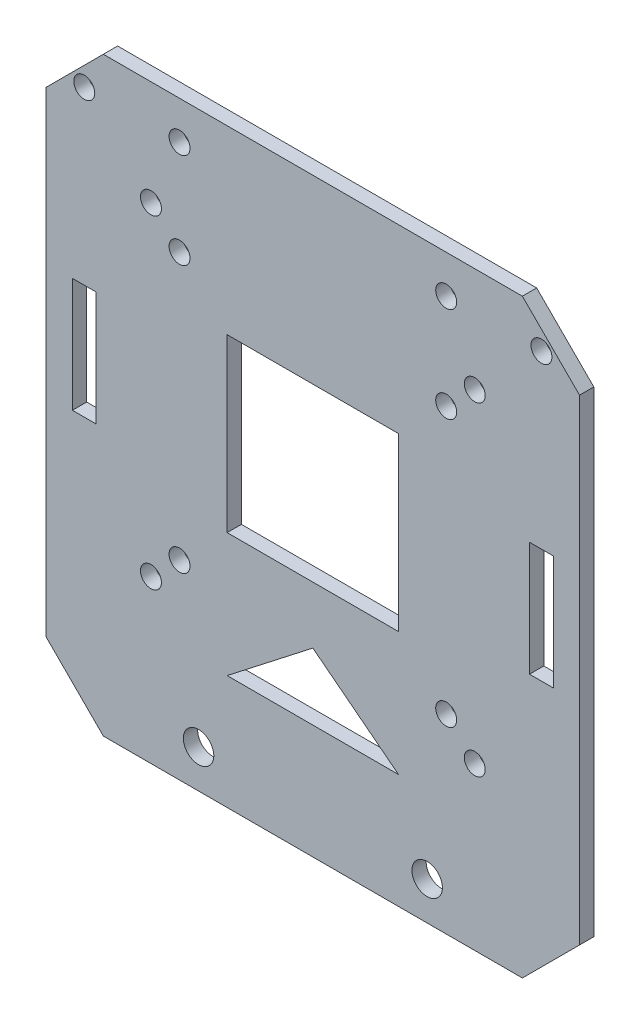
SolidWorks part; units mm, degrees
material "碳纤维板_1600kg_m3"
ref_plane "前视基准面" through (0, 0, 0) normal (0, 0, 1) x (1, 0, 0)
ref_plane "上视基准面" through (0, 0, 0) normal (0, 1, 0) x (1, 0, 0)
ref_plane "右视基准面" through (0, 0, 0) normal (1, 0, 0) x (0, 0, -1)
other "Configuration Table"
sketch "草图1" plane through (0, 0, 0) normal (0, 0, 1) x (1, 0, 0)
  line L0 (-22, 4) -> (22, 4)
  line L1 (22, 4) -> (28, 10)
  line L2 (28, 10) -> (28, 60)
  line L3 (28, 60) -> (22, 66)
  line L4 (22, 66) -> (-22, 66)
  line L5 (-22, 66) -> (-28, 60)
  line L6 (-28, 60) -> (-28, 10)
  line L7 (-28, 10) -> (-22, 4)
  line L8 (-25.25, 32) -> (-22.75, 32)
  line L9 (-22.75, 32) -> (-22.75, 44)
  line L10 (-22.75, 44) -> (-25.25, 44)
  line L11 (-25.25, 44) -> (-25.25, 32)
  line L12 (22.75, 32) -> (25.25, 32)
  line L13 (25.25, 32) -> (25.25, 44)
  line L14 (25.25, 44) -> (22.75, 44)
  line L15 (22.75, 44) -> (22.75, 32)
  line L16 (-9, 29) -> (9, 29)
  line L17 (9, 29) -> (9, 47)
  line L18 (9, 47) -> (-9, 47)
  line L19 (-9, 47) -> (-9, 29)
  line L20 (-9, 16) -> (9, 16)
  line L21 (9, 16) -> (0, 23)
  line L22 (0, 23) -> (-9, 16)
  circle A0 centre (-12, 8) radius 1.6
  circle A1 centre (-24, 62) radius 1.1
  circle A2 centre (12, 8) radius 1.6
  circle A3 centre (24, 62) radius 1.1
  circle A4 centre (-14, 24) radius 1.1
  circle A5 centre (-14, 52) radius 1.1
  circle A6 centre (14, 24) radius 1.1
  circle A7 centre (14, 52) radius 1.1
  circle A8 centre (-17, 21) radius 1.1
  circle A9 centre (-17, 55) radius 1.1
  circle A10 centre (17, 21) radius 1.1
  circle A11 centre (17, 55) radius 1.1
extrude "几何切角镂空摄像头板_双孔距_钢索孔" add sketch "草图1" along normal blind 1.5
sketch "草图2" plane through (0, 0, 0) normal (0, 0, 1) x (1, 0, 0)
  circle A0 centre (-14, 62) radius 1.1
  circle A1 centre (14, 62) radius 1.1
extrude "外拉钢索两孔_D2p2" cut sketch "草图2" along normal blind 1.5
